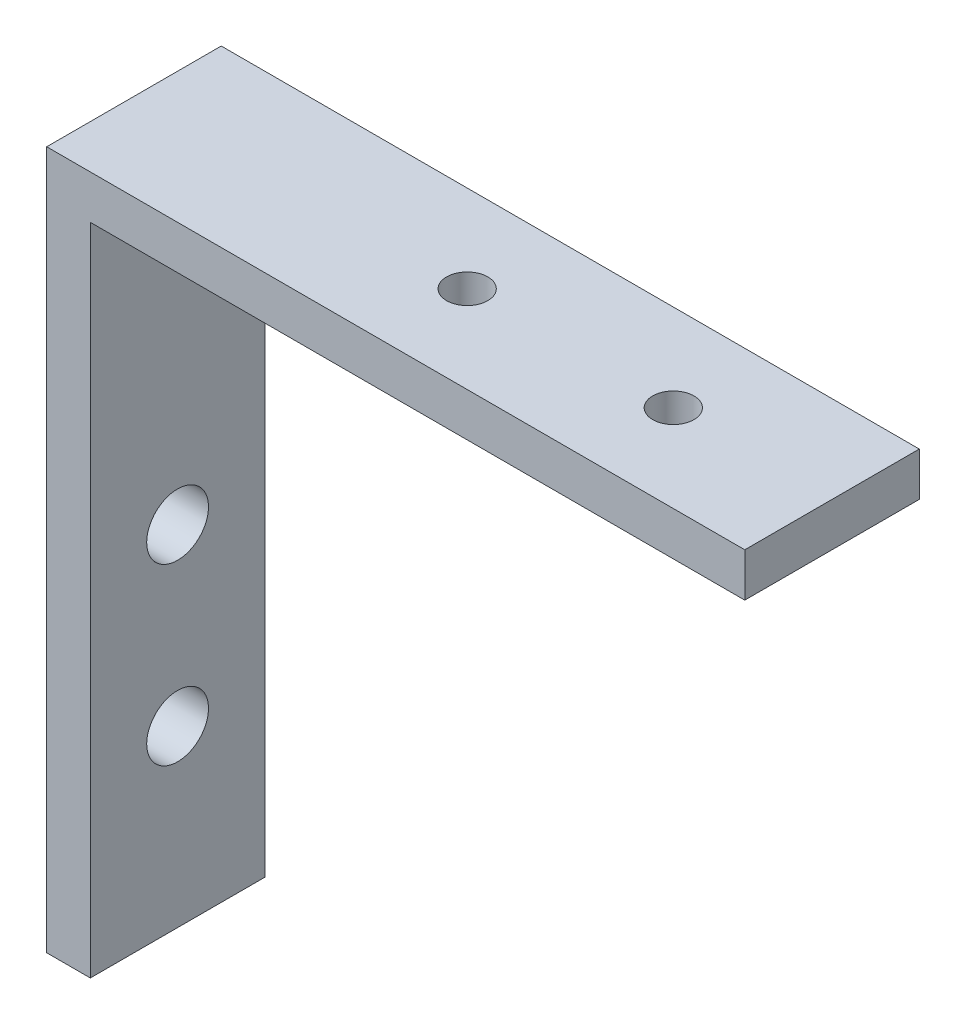
SolidWorks part; units mm, degrees
ref_plane "Front Plane" through (0, 0, 0) normal (0, 0, 1) x (1, 0, 0)
ref_plane "Top Plane" through (0, 0, 0) normal (0, 1, 0) x (1, 0, 0)
ref_plane "Right Plane" through (0, 0, 0) normal (1, 0, 0) x (0, 0, -1)
sketch "Sketch1" plane through (0, 0, 0) normal (0, 0, 1) x (1, 0, 0)
  line L0 (0, 0) -> (0, 50.8)
  line L1 (0, 50.8) -> (50.8, 50.8)
  dimension "D1" = 50.8
  dimension "D2" = 50.8
extrude "Extrude-Thin1" add sketch "Sketch1" along normal blind 12.7 thin
sketch "Sketch2" plane through (0, 0, 0) normal (-1, 0, 0) x (0, 0, 1)
  line L0 (6.35, 50.8) -> (6.35, 0) construction
  line L1 (12.7, 50.8) -> (0, 50.8) construction
  line L2 (12.7, 0) -> (0, 0) construction
  line L3 (0, 50.8) -> (12.7, 50.8) construction
  line L4 (0, 50.8) -> (12.7, 50.8) construction
  line L5 (0, 38.1) -> (12.7, 38.1) construction
  line L6 (0, 25.4) -> (12.7, 25.4) construction
  line L7 (0, 12.7) -> (12.7, 12.7) construction
  circle A0 centre (6.35, 12.7) radius 2.25
  circle A1 centre (6.35, 25.4) radius 2.25
  dimension "D2" = 4.5
  dimension "D3" = 4.5
  dimension "D1" = 4
extrude "Cut-Extrude1" cut sketch "Sketch2" against normal up to next
sketch "Sketch6" plane through (0, 50.8, 0) normal (0, 1, 0) x (1, 0, 0)
  line L0 (31.75, -12.7) -> (31.75, 0) construction
  line L1 (50.8, -12.7) -> (50.8, 0) construction
  line L2 (0, -12.7) -> (50.8, -12.7) construction
  line L5 (0, 0) -> (50.8, 0) construction
  line L6 (0, -6.35) -> (50.8, -6.35) construction
  line L8 (0, -12.7) -> (0, 0) construction
  line L9 (50.8, 0) -> (50.8, -12.7) construction
  circle A0 centre (31.75, -6.35) radius 7.5 construction
  circle A1 centre (24.25, -6.35) radius 1.5
  circle A2 centre (39.25, -6.35) radius 1.5
  dimension "D1" = 19.05
  dimension "D2" = 15
  dimension "D3" = 3
  dimension "D4" = 3
extrude "Cut-Extrude2" cut sketch "Sketch6" against normal up to next
